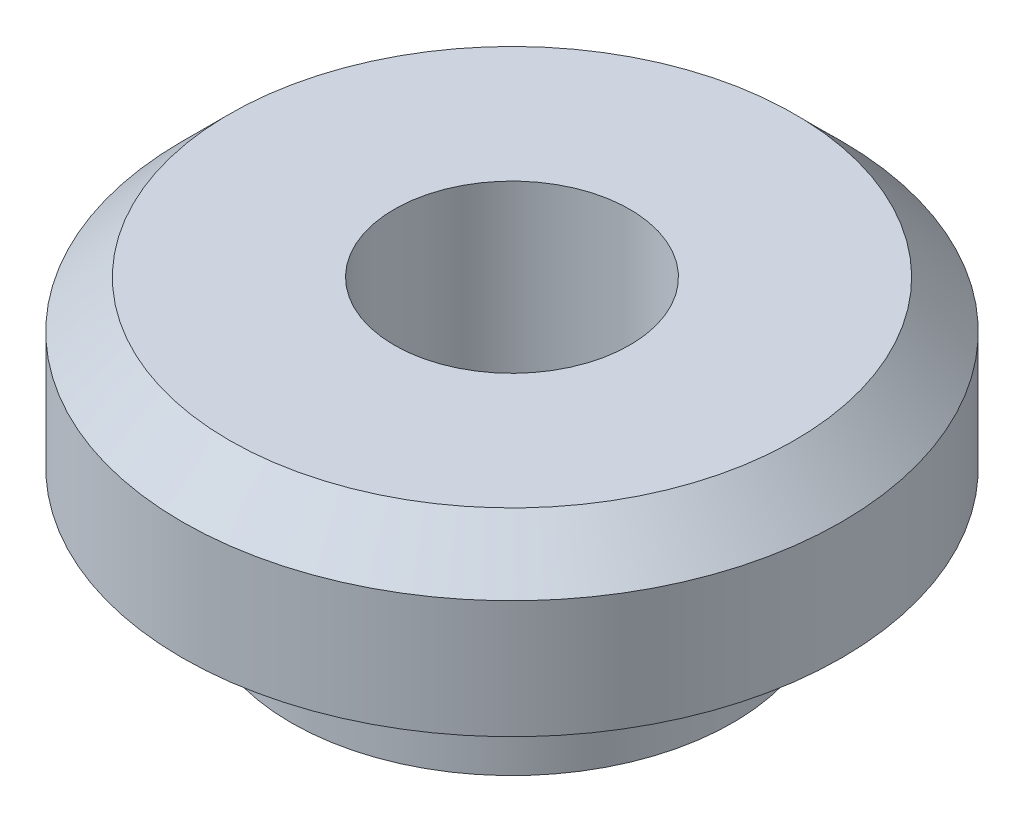
SolidWorks part; units mm, degrees
ref_plane "Front" through (0, 0, 0) normal (0, 0, 1) x (1, 0, 0)
ref_plane "Top" through (0, 0, 0) normal (0, 1, 0) x (1, 0, 0)
ref_plane "Side" through (0, 0, 0) normal (1, 0, 0) x (0, 0, -1)
other "Configuration Table"
sketch "Sketch1" plane through (0, 0, 0) normal (1, 0, 0) x (0, 0, -1)
  line L0 (0, 40) -> (0, -40) construction
  line L1 (-1.27, 1.778) -> (-1.27, -1.1938)
  line L2 (-1.27, 1.778) -> (-3.048, 1.778)
  line L3 (-3.048, 1.778) -> (-3.556, 1.27)
  line L4 (-3.556, 1.27) -> (-3.556, 0)
  line L5 (-3.556, 0) -> (-2.3812, 0)
  line L6 (-2.3812, 0) -> (-2.3812, -1.1938)
  line L7 (-2.3812, -1.1938) -> (-1.27, -1.1938)
  dimension "D1" = 1.778
  dimension "D2" = 2.9718
  dimension "D3" = 1.27
  dimension "D4" = 2.3812
  dimension "D5" = 3.556
  dimension "D6" = 0.508
  dimension "D7" = 0.508
  dimension "D8" = 1.1748
revolve "Boss-Revolve1" add sketch "Sketch1" angle 360 about L0
cosmetic thread "Cosmetic Thread1" parameters "D2"=2.54
cosmetic thread "Cosmetic Thread2" parameters "D2"=4.064
